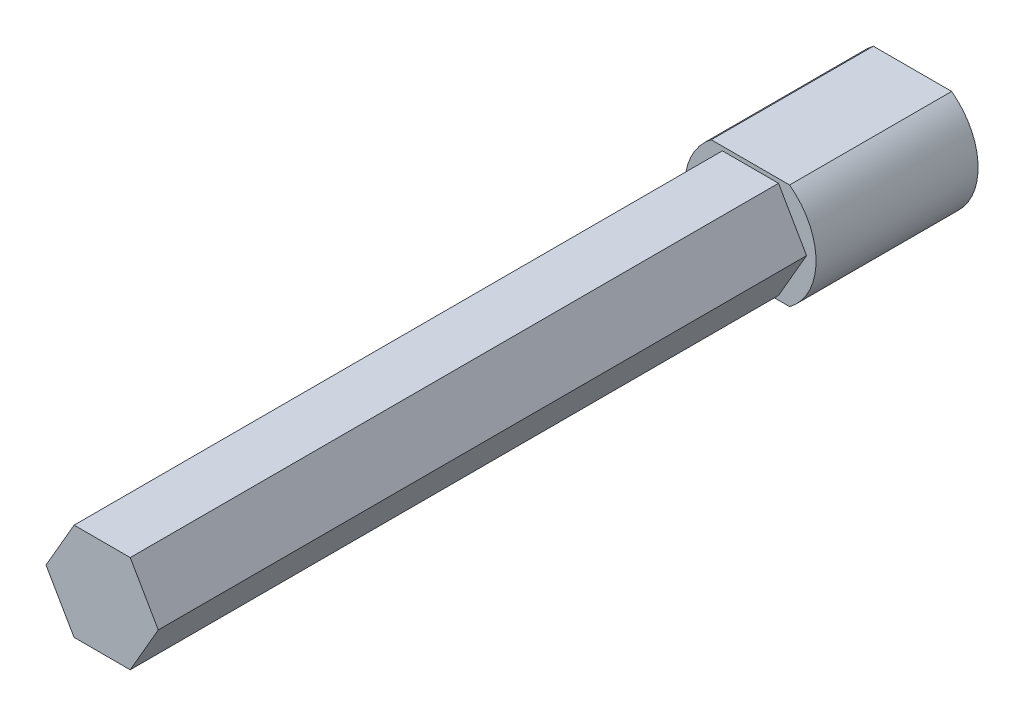
SolidWorks part; units mm, degrees
ref_plane "Front Plane" through (0, 0, 0) normal (0, 0, 1) x (1, 0, 0)
ref_plane "Top Plane" through (0, 0, 0) normal (0, 1, 0) x (1, 0, 0)
ref_plane "Right Plane" through (0, 0, 0) normal (1, 0, 0) x (0, 0, -1)
sketch "Sketch1" plane through (0, 0, 0) normal (0, 0, 1) x (1, 0, 0)
  line L0 (-2.4166, 3.25) -> (2.4166, 3.25)
  line L1 (-2.4166, -3.25) -> (2.4166, -3.25)
  arc A0 (-2.4166, 3.25) -> (-2.4166, -3.25) centre (0, 0) ccw
  arc A2 (2.4166, -3.25) -> (2.4166, 3.25) centre (0, 0) ccw
  dimension "D1" = 8.1
  dimension "D3" = 6.5
extrude "Boss-Extrude2" add sketch "Sketch1" along normal blind 10
sketch "Sketch3" plane through (0, 0, 0) normal (0, 0, -1) x (-1, 0, 0)
  line L2 (2.4166, 3.25) -> (-2.4166, 3.25)
  line L3 (-2.4166, -3.25) -> (2.4166, -3.25)
  line L4 (2.4166, 3.25) -> (-2.4166, 3.25)
  line L5 (-2.4166, -3.25) -> (2.4166, -3.25)
  line L6 (2.1541, 2.5) -> (-2.1541, 2.5)
  line L7 (-2.1541, -2.5) -> (2.1541, -2.5)
  arc A2 (2.4166, -3.25) -> (2.4166, 3.25) centre (0, 0) ccw
  arc A3 (-2.4166, 3.25) -> (-2.4166, -3.25) centre (0, 0) ccw
  arc A4 (2.4166, -3.25) -> (2.4166, 3.25) centre (0, 0) ccw
  arc A5 (-2.4166, 3.25) -> (-2.4166, -3.25) centre (0, 0) ccw
  arc A6 (-2.1541, 2.5) -> (-2.1541, -2.5) centre (0, 0) ccw
  arc A7 (2.1541, -2.5) -> (2.1541, 2.5) centre (0, 0) ccw
  dimension "D1" = 0
  dimension "D3" = 0.75
sketch "Sketch4" plane through (0, 0, 10) normal (0, 0, 1) x (1, 0, 0)
  line L1 (1.7303, -3.001) -> (3.4641, -0.0021)
  line L2 (3.4641, -0.0021) -> (1.7339, 2.999)
  line L3 (1.7339, 2.999) -> (-1.7303, 3.001)
  line L4 (-1.7303, 3.001) -> (-3.4641, 0.0021)
  line L5 (-3.4641, 0.0021) -> (-1.7339, -2.999)
  line L6 (-1.7339, -2.999) -> (1.7303, -3.001)
  circle A0 centre (0, 0) radius 3 construction
  dimension "D1" = 6
extrude "Boss-Extrude3" add sketch "Sketch4" along normal blind 40
extrude "Cut-Extrude1" cut sketch "Sketch3" against normal blind 5 contours L6 A6 L7 A7
